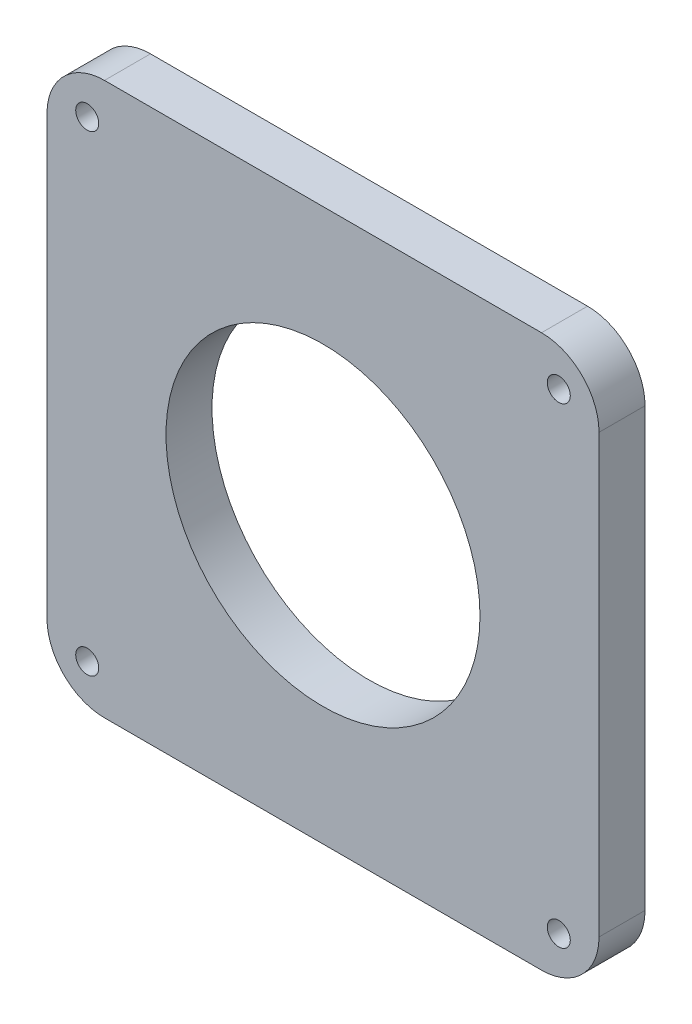
SolidWorks part; units mm, degrees
ref_plane "Front Plane" through (0, 0, 0) normal (0, 0, 1) x (1, 0, 0)
ref_plane "Top Plane" through (0, 0, 0) normal (0, 1, 0) x (1, 0, 0)
ref_plane "Right Plane" through (0, 0, 0) normal (1, 0, 0) x (0, 0, -1)
sketch "Sketch1" plane through (0, 0, 0) normal (0, 0, 1) x (1, 0, 0)
  line L0 (0, 0) -> (96, 0)
  line L1 (96, 0) -> (96, 96)
  line L2 (96, 96) -> (0, 96)
  line L3 (0, 96) -> (0, 0)
  dimension "D1" = 96
  dimension "D2" = 96
extrude "Boss-Extrude1" add sketch "Sketch1" along normal blind 0.6
sketch "Sketch2" plane through (0, 0, 0.6) normal (0, 0, 1) x (1, 0, 0)
  line L4 (10, 96) -> (0, 96)
  line L5 (0, 96) -> (0, 86)
  line L6 (86, 96) -> (96, 96)
  line L7 (96, 96) -> (96, 86)
  line L8 (86, 0) -> (96, 0)
  line L9 (96, 0) -> (96, 10)
  line L10 (0, 0) -> (10, 0)
  line L11 (0, 0) -> (0, 10)
  arc A0 (10, 0) -> (0, 10) centre (10, 10) cw
  arc A1 (96, 10) -> (86, 0) centre (86, 10) cw
  arc A2 (86, 96) -> (96, 86) centre (86, 86) cw
  arc A3 (10, 96) -> (0, 86) centre (10, 86) ccw
  point P10 (0, 0)
  point P13 (96, 0)
  point P16 (96, 96)
  point P19 (0, 96)
  dimension "D1" = 10
extrude "Cut-Extrude1" cut sketch "Sketch2" against normal blind 74.6
sketch "Sketch3" plane through (0, 0, 0.6) normal (0, 0, 1) x (1, 0, 0)
  line L0 (48, 96) -> (48, 0) construction
  line L1 (86, 96) -> (10, 96) construction
  line L2 (10, 0) -> (86, 0) construction
  circle A0 centre (48, 48) radius 27.3
  dimension "D1" = 54.6
extrude "Cut-Extrude2" cut sketch "Sketch3" against normal blind 74.6
sketch "Sketch4" plane through (0, 0, 0) normal (0, 0, -1) x (-1, 0, 0)
  circle A0 centre (-89, 89) radius 2
  circle A1 centre (-7, 89) radius 2
  circle A2 centre (-7, 7) radius 2
  circle A3 centre (-89, 7) radius 2
  point P0 (-48, 48)
  dimension "D3" = 4
  dimension "D4" = 4
  dimension "D5" = 4
  dimension "D6" = 4
extrude "Cut-Extrude3" cut sketch "Sketch4" against normal blind 74.6
sketch "Sketch5" plane through (0, 0, 0.6) normal (0, 0, 1) x (1, 0, 0)
  circle A0 centre (48, 48) radius 27.3
  circle A1 centre (48, 48) radius 37.3
  dimension "D1" = 10
extrude "Boss-Extrude3" add sketch "Sketch5" along normal blind 2.5 draft 42
sketch "Sketch7" plane through (0, 0, 0) normal (0, 0, -1) x (-1, 0, 0)
  circle A0 centre (-48, 48) radius 32
  dimension "D1" = 64
sketch "Sketch8" plane through (0, 0, 0.6) normal (0, 0, 1) x (1, 0, 0)
  line L4 (0, 86) -> (0, 10)
  line L5 (10, 0) -> (86, 0)
  line L6 (96, 10) -> (96, 86)
  line L7 (86, 96) -> (10, 96)
  line L8 (0, 86) -> (0, 10)
  line L9 (10, 0) -> (86, 0)
  line L10 (96, 10) -> (96, 86)
  line L11 (86, 96) -> (10, 96)
  circle A0 centre (48, 48) radius 27.3 construction
  circle A1 centre (48, 48) radius 27.3
  arc A4 (10, 96) -> (0, 86) centre (10, 86) ccw
  arc A5 (0, 10) -> (10, 0) centre (10, 10) ccw
  arc A6 (86, 0) -> (96, 10) centre (86, 10) ccw
  arc A7 (96, 86) -> (86, 96) centre (86, 86) ccw
  arc A8 (10, 96) -> (0, 86) centre (10, 86) ccw
  arc A9 (0, 10) -> (10, 0) centre (10, 10) ccw
  arc A10 (86, 0) -> (96, 10) centre (86, 10) ccw
  arc A11 (96, 86) -> (86, 96) centre (86, 86) ccw
  dimension "D1" = 0
extrude "Boss-Extrude4" add sketch "Sketch8" along normal blind 7.4
sketch "Sketch9" plane through (0, 0, 0) normal (0, 0, -1) x (-1, 0, 0)
  circle A0 centre (-7, 89) radius 2 construction
  circle A1 centre (-89, 89) radius 2 construction
  circle A2 centre (-89, 7) radius 2 construction
  circle A3 centre (-7, 7) radius 2 construction
  circle A4 centre (-7, 89) radius 2
  circle A5 centre (-89, 89) radius 2
  circle A6 centre (-89, 7) radius 2
  circle A7 centre (-7, 7) radius 2
extrude "Cut-Extrude4" cut sketch "Sketch9" against normal through all
